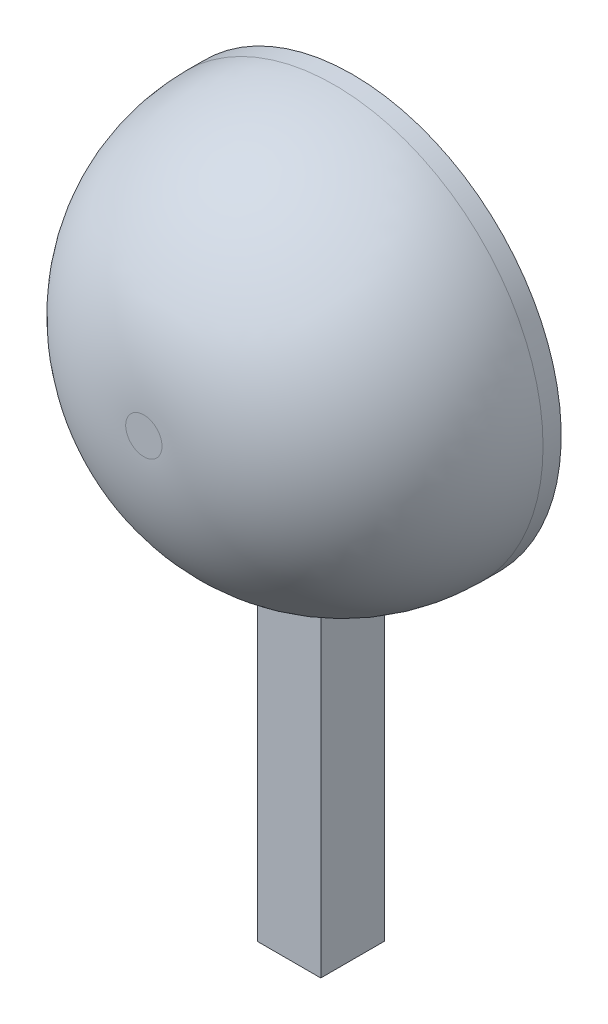
SolidWorks part; units mm, degrees
ref_plane "Front Plane" through (0, 0, 0) normal (0, 0, 1) x (1, 0, 0)
ref_plane "Top Plane" through (0, 0, 0) normal (0, 1, 0) x (1, 0, 0)
ref_plane "Right Plane" through (0, 0, 0) normal (1, 0, 0) x (0, 0, -1)
sketch "Sketch2" plane through (0, 0, 0) normal (0, 0, 1) x (1, 0, 0)
  line L0 (-24.3651, 0) -> (30.0337, 0)
  circle A0 centre (0, 23) radius 23
  dimension "D1" = 46
extrude "Boss-Extrude1" add sketch "Sketch2" along normal blind 23 contours A0
fillet "Fillet1" radius 21 1 edges at (23, 23, 23)
shell "Shell1" thickness 4
fillet "Fillet2" radius 1 1 edges at (19, 23, 0)
ref_plane "Plane1" through (0, 0, 0) normal (0, 1, 0) x (1, 0, 0)
sketch "Sketch5" plane through (0, 0, 0) normal (0, 1, 0) x (1, 0, 0)
  line L0 (-3.5, 0) -> (3.5, 0)
  line L1 (-24.3651, 0) -> (30.0337, 0) construction
  line L2 (-3.5, 0) -> (-3.5, -7)
  line L3 (-3.5, -7) -> (3.5, -7)
  line L4 (3.5, -7) -> (3.5, 0)
  point P4 (0, 0)
  dimension "D1" = 7
  dimension "D2" = 7
extrude "Boss-Extrude3" add sketch "Sketch5" against normal blind 35 and the other way blind 3
